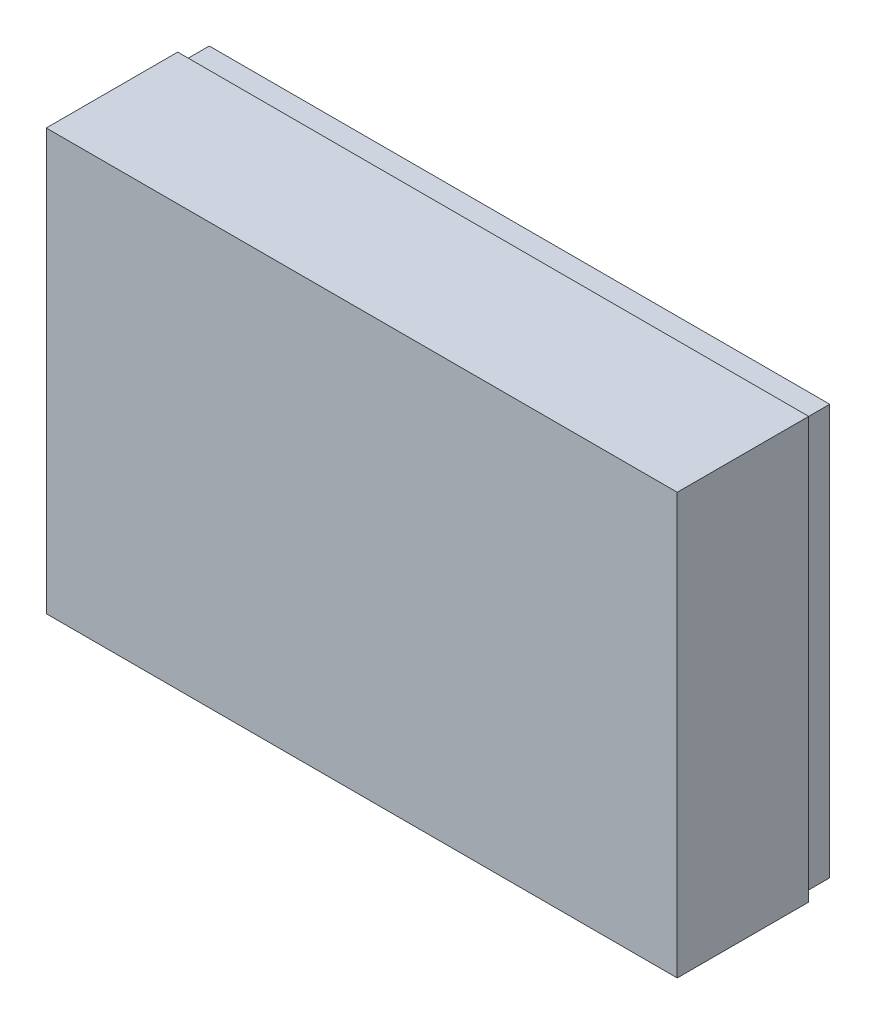
SolidWorks part; units mm, degrees
material "PVC Rigid"
ref_plane "Front Plane" through (0, 0, 0) normal (0, 0, 1) x (1, 0, 0)
ref_plane "Top Plane" through (0, 0, 0) normal (0, 1, 0) x (1, 0, 0)
ref_plane "Right Plane" through (0, 0, 0) normal (1, 0, 0) x (0, 0, -1)
sketch "Sketch1" plane through (0, 0, 0) normal (0, 0, 1) x (1, 0, 0)
  line L1 (60, 40) -> (-60, 40)
  line L2 (60, 40) -> (60, -40)
  line L3 (60, -40) -> (-60, -40)
  line L4 (-60, 40) -> (-60, -40)
  line L5 (60, 40) -> (-60, -40) construction
  line L6 (60, -40) -> (-60, 40) construction
  point P0 (0, 0)
extrude "Boss-Extrude1" add sketch "Sketch1" along normal blind 30
shell "Shell1" thickness 2
sketch "Sketch9" plane through (0, 0, 0) normal (0, 0, -1) x (-1, 0, 0)
  line L4 (60, -40) -> (60, 40)
  line L5 (60, 40) -> (-60, 40)
  line L6 (-60, 40) -> (-60, -40)
  line L7 (-60, -40) -> (60, -40)
  line L8 (60, -40) -> (60, 40)
  line L9 (60, 40) -> (-60, 40)
  line L10 (-60, 40) -> (-60, -40)
  line L11 (-60, -40) -> (60, -40)
  line L12 (58, 38) -> (58, -38) construction
  dimension "D1" = 0
sketch "Sketch10" plane through (0, 0, 0) normal (0, 0, -1) x (-1, 0, 0)
  line L0 (59, -39) -> (59, 39)
  line L1 (59, 39) -> (-59, 39)
  line L2 (-59, 39) -> (-59, -39)
  line L3 (-59, -39) -> (59, -39)
  line L4 (60, -40) -> (60, 40)
  line L5 (60, 40) -> (-60, 40)
  line L6 (-60, 40) -> (-60, -40)
  line L7 (-60, -40) -> (60, -40)
  line L8 (60, -40) -> (60, 40)
  line L9 (60, 40) -> (-60, 40)
  line L10 (-60, 40) -> (-60, -40)
  line L11 (-60, -40) -> (60, -40)
  dimension "D1" = 0
  dimension "D2" = 1
extrude "Cut-Extrude1" cut sketch "Sketch10" against normal blind 5
